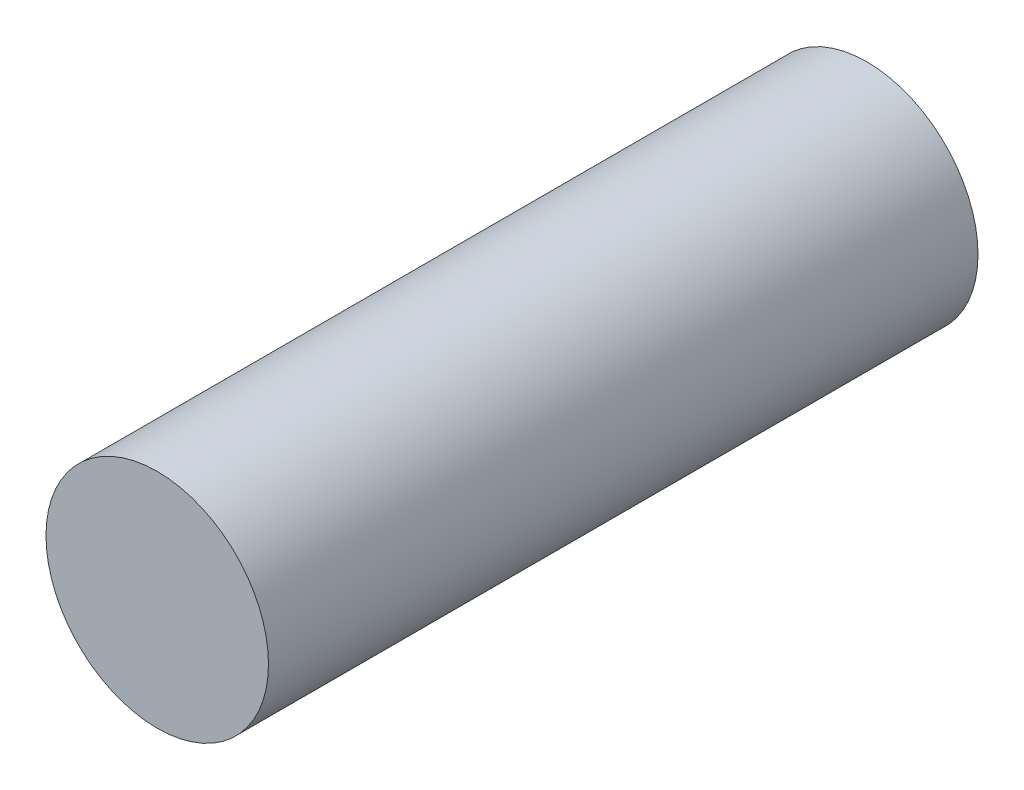
SolidWorks part; units mm, degrees
material "Alloy Steel"
ref_plane "Front Plane" through (0, 0, 0) normal (0, 0, 1) x (1, 0, 0)
ref_plane "Top Plane" through (0, 0, 0) normal (0, 1, 0) x (1, 0, 0)
ref_plane "Right Plane" through (0, 0, 0) normal (1, 0, 0) x (0, 0, -1)
sketch "Sketch1" plane through (0, 0, 0) normal (0, 0, 1) x (1, 0, 0)
  circle A0 centre (0, 0) radius 4.17
  dimension "D1" = 8.34
extrude "Boss-Extrude1" add sketch "Sketch1" along normal mid plane 26.6
